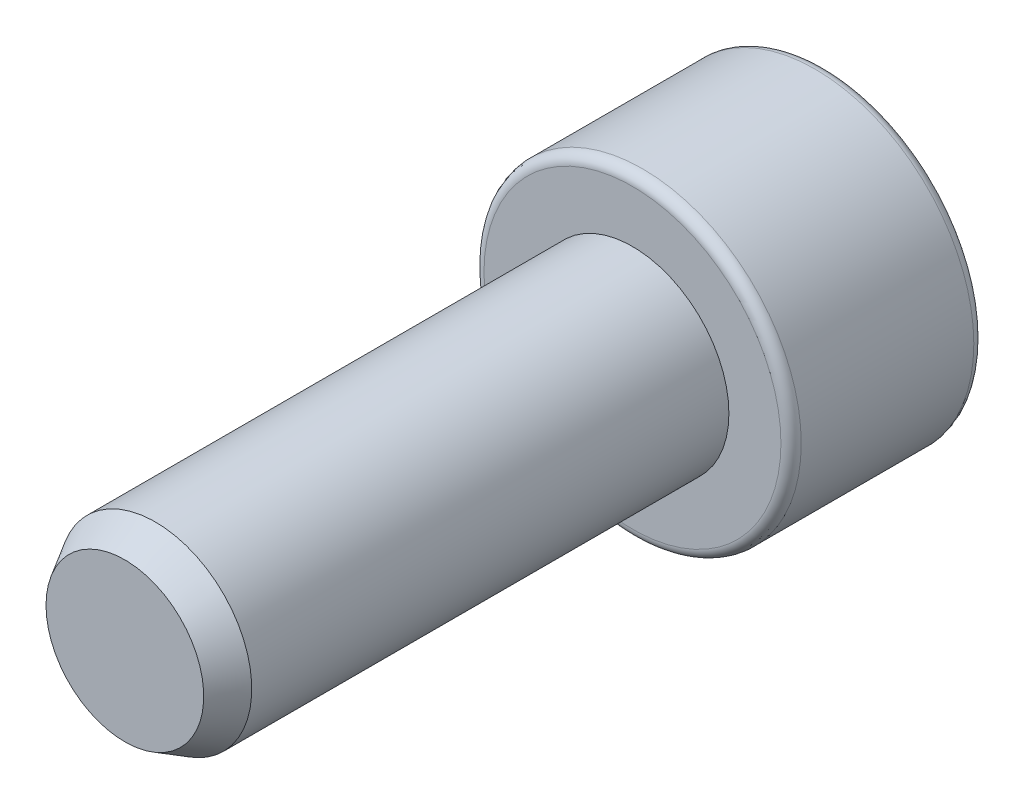
SolidWorks part; units mm, degrees
ref_plane "Front Plane" through (0, 0, 0) normal (0, 0, 1) x (1, 0, 0)
ref_plane "Top Plane" through (0, 0, 0) normal (0, 1, 0) x (1, 0, 0)
ref_plane "Right Plane" through (0, 0, 0) normal (1, 0, 0) x (0, 0, -1)
sketch "Sketch1" plane through (0, 0, 0) normal (0, 1, 0) x (1, 0, 0)
  line L0 (0, 0) -> (3.7147, 0)
  line L1 (3.9687, -0.254) -> (3.9687, -4.572)
  line L2 (3.7147, -4.826) -> (0, -4.826)
  line L3 (0, 0) -> (0, 1.0712) construction
  line L4 (0, 0) -> (0, -4.826)
  line L5 (0, 0) -> (0.1848, 0.1731) construction
  arc A0 (3.9687, -4.572) -> (3.7147, -4.826) centre (3.7147, -4.572) cw
  arc A1 (3.9687, -0.254) -> (3.7147, 0) centre (3.7147, -0.254) ccw
  point P6 (3.9687, -4.826)
  point P9 (3.9687, 0)
revolve "Revolve1" add sketch "Sketch1" angle 360 about L3
sketch "Sketch2" plane through (0, 0, 0) normal (0, 0, -1) x (-1, 0, 0)
  line L1 (0, 2.2914) -> (-1.9844, 1.1457)
  line L2 (-1.9844, 1.1457) -> (-1.9844, -1.1457)
  line L3 (-1.9844, -1.1457) -> (0, -2.2914)
  line L4 (0, -2.2914) -> (1.9844, -1.1457)
  line L5 (1.9844, -1.1457) -> (1.9844, 1.1457)
  line L6 (1.9844, 1.1457) -> (0, 2.2914)
  circle A0 centre (0, 0) radius 1.9844 construction
extrude "Cut-Extrude1" cut sketch "Sketch2" against normal blind 2.54
sketch "Sketch3" plane through (0, 0, 4.826) normal (0, 0, 1) x (1, 0, 0)
  circle A0 centre (0, 0) radius 2.413
  dimension "D1" = 4.826
extrude "Boss-Extrude1" add sketch "Sketch3" along normal blind 12.7
chamfer "Chamfer1" distance 0.762 angle 30 1 edges at (2.413, 0, 17.526)
